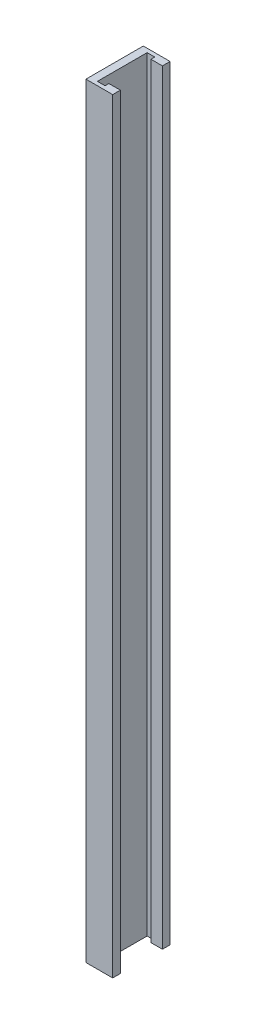
SolidWorks part; units mm, degrees
ref_plane "Alzado" through (0, 0, 0) normal (0, 0, 1) x (1, 0, 0)
ref_plane "Planta" through (0, 0, 0) normal (0, 1, 0) x (1, 0, 0)
ref_plane "Vista lateral" through (0, 0, 0) normal (1, 0, 0) x (0, 0, -1)
sketch "Croquis1" plane through (0, 0, 0) normal (1, 0, 0) x (0, 0, -1)
  line L1 (-13.7368, 28.0263) -> (1.2632, 28.0263)
  line L2 (-13.7368, 28.0263) -> (-13.7368, -171.9737)
  line L3 (-13.7368, -171.9737) -> (1.2632, -171.9737)
  line L4 (1.2632, 28.0263) -> (1.2632, -171.9737)
  dimension "D1" = 15
  dimension "D2" = 200
extrude "Saliente-Extruir1" add sketch "Croquis1" along normal blind 7
sketch "Croquis2" plane through (0, 28.0263, 0) normal (0, 1, 0) x (1, 0, 0)
  line L0 (0, -6.2368) -> (7, -6.2368) construction
  line L1 (0, 1.2632) -> (0, -13.7368) construction
  line L2 (7, 1.2632) -> (7, -13.7368) construction
  line L3 (7, -0.7368) -> (4, -0.7368)
  line L4 (4, -0.7368) -> (4, 0.2632)
  line L5 (4, 0.2632) -> (2, 0.2632)
  line L6 (2, 0.2632) -> (2, -12.7368)
  line L7 (7, 1.2632) -> (0, 1.2632) construction
  line L8 (4, -11.7368) -> (4, -12.7368)
  line L9 (7, -11.7368) -> (4, -11.7368)
  line L10 (4, -12.7368) -> (2, -12.7368)
  line L11 (7, -0.7368) -> (7, -11.7368)
  point P17 (2, -6.2368)
  dimension "D1" = 5
  dimension "D2" = 2
  dimension "D3" = 3
  dimension "D4" = 6.5
extrude "Cortar-Extruir1" cut sketch "Croquis2" against normal through all
